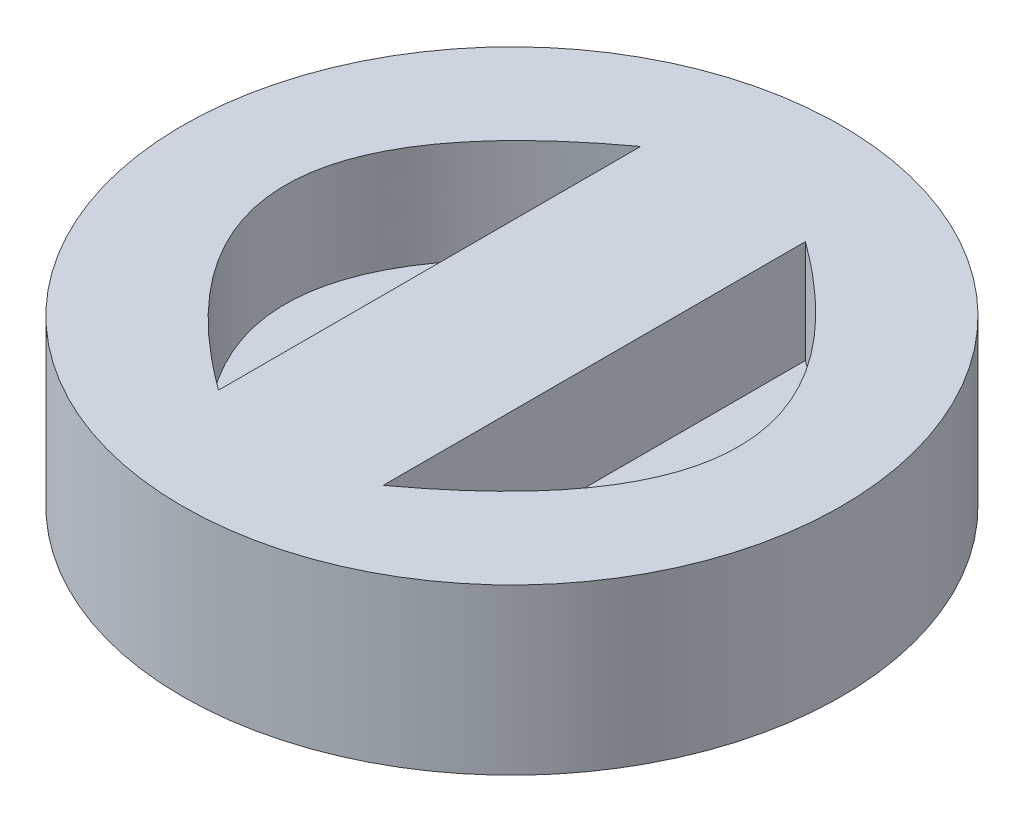
SolidWorks part; units mm, degrees
ref_plane "Front Plane" through (0, 0, 0) normal (0, 0, 1) x (1, 0, 0)
ref_plane "Top Plane" through (0, 0, 0) normal (0, 1, 0) x (1, 0, 0)
ref_plane "Right Plane" through (0, 0, 0) normal (1, 0, 0) x (0, 0, -1)
sketch "Sketch1" plane through (0, 0, 0) normal (0, 1, 0) x (1, 0, 0)
  circle A0 centre (-62.4172, 31.4468) radius 16
  dimension "D1" = 32
extrude "Boss-Extrude1" add sketch "Sketch1" along normal blind 8
sketch "Sketch7" plane through (0, 8, 0) normal (0, 1, 0) x (1, 0, 0)
  line L0 (-66.4172, 41.6938) -> (-66.4172, 21.1999)
  line L5 (-58.4172, 41.6938) -> (-58.4172, 21.1999)
  line L6 (-62.4172, 42.4468) -> (-62.4172, 20.4468)
  line L7 (-51.4172, 31.4468) -> (-73.4172, 31.4468)
  circle A1 centre (-62.4172, 31.4468) radius 11
  circle A2 centre (-62.4172, 31.4468) radius 16 construction
  spline S0 degree 2 poles (-66.4172, 41.6938) (-62.4172, 43.1999) (-58.4172, 41.6938) knots 0 0 0 1 1 1
  spline S1 degree 3 poles (-58.4172, 21.1999) (-59.7506, 20.8234) (-62.4172, 20.0703) (-65.0839, 20.8234) (-66.4172, 21.1999) knots 0 0 0 0 0.5 1 1 1 1
  point P4 (-62.4172, 31.8086)
  point P5 (-62.4172, 31.7305)
  point P6 (-62.4172, 31.7305)
  point P7 (-62.4172, 31.7305)
  dimension "D1" = 0
  dimension "D2" = 5
  dimension "D3" = 8
  dimension "D4" = 4
sketch "Sketch9" plane through (0, 8, 0) normal (0, 1, 0) x (1, 0, 0)
  line L0 (-66.4172, 41.6938) -> (-66.4172, 31.4468)
  line L1 (-66.4172, 41.6938) -> (-66.4172, 21.1999) construction
  line L2 (-66.4172, 31.4468) -> (-66.4172, 21.1999)
  line L3 (-58.4172, 41.6938) -> (-58.4172, 21.1999)
  spline S0 degree 2 poles (-58.4172, 41.6938) (-44.4172, 31.4468) (-58.4172, 21.1999) knots 0 0 0 1 1 1
  spline S1 degree 2 poles (-66.4172, 41.6938) (-80.4172, 31.4468) (-66.4172, 21.1999) knots 0 0 0 1 1 1
extrude "Cut-Extrude2" cut sketch "Sketch9" against normal blind 5
